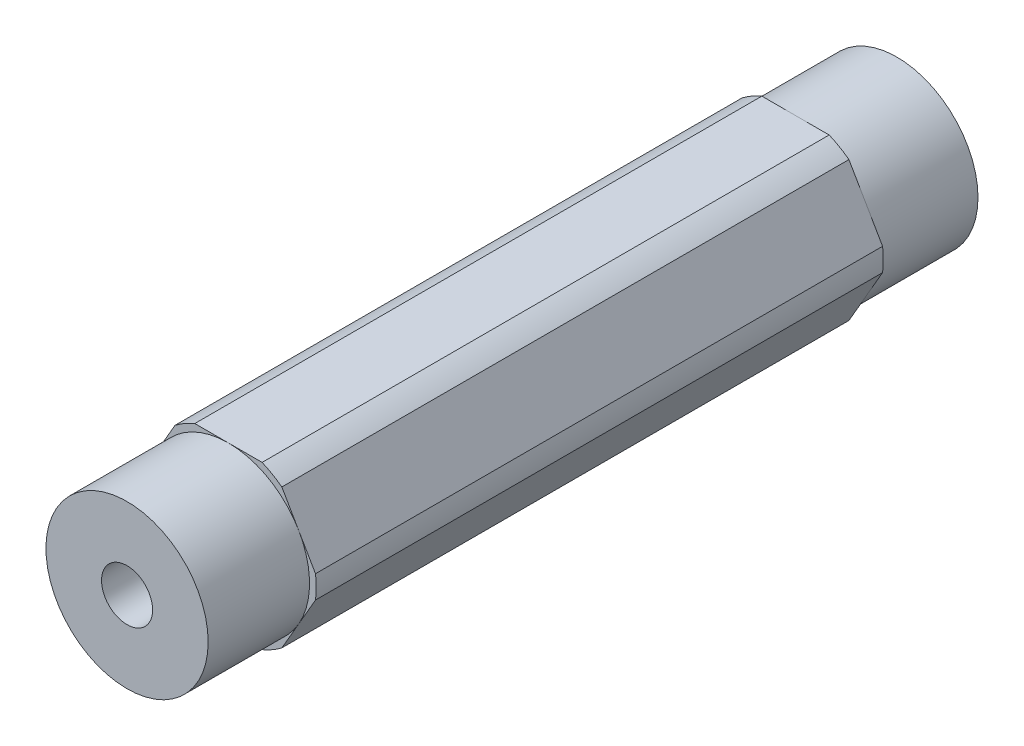
SolidWorks part; units mm, degrees
material "6061-T6 (SS)"
ref_plane "Front Plane" through (0, 0, 0) normal (0, 0, 1) x (1, 0, 0)
ref_plane "Top Plane" through (0, 0, 0) normal (0, 1, 0) x (1, 0, 0)
ref_plane "Right Plane" through (0, 0, 0) normal (1, 0, 0) x (0, 0, -1)
sketch "Sketch1" plane through (0, 0, 0) normal (0, 0, 1) x (1, 0, 0)
  line L1 (3.6662, 6.35) -> (-3.6662, 6.35)
  line L2 (-3.6662, 6.35) -> (-7.3323, 0)
  line L3 (-7.3323, 0) -> (-3.6662, -6.35)
  line L4 (-3.6662, -6.35) -> (3.6662, -6.35)
  line L5 (3.6662, -6.35) -> (7.3323, 0)
  line L6 (7.3323, 0) -> (3.6662, 6.35)
  circle A0 centre (0, 0) radius 6.35 construction
  circle A1 centre (0, 0) radius 2
  circle A2 centre (0, 0) radius 6.875
  point P1 (0, 6.35)
  dimension "D2" = 13.75
  dimension "D3" = 4
  dimension "D1" = 12.7
extrude "Boss-Extrude1" add sketch "Sketch1" along normal mid plane 44.3992 contours L6 A2 L1 L2 L3 L4 L5 A1
sketch "Sketch4" plane through (0, 0, 22.1996) normal (0, 0, 1) x (1, 0, 0)
  circle A0 centre (0, 0) radius 6.35
  circle A1 centre (0, 0) radius 2 construction
  circle A2 centre (0, 0) radius 2
  dimension "D1" = 12.7
extrude "Boss-Extrude2" add sketch "Sketch4" along normal blind 7.9375
mirror "Mirror1" about plane through (0, 0, 0) normal (0, 0, 1) of "Boss-Extrude2"
equation "\"D2@Sketch1\"=13.75mm"
equation "\"D3@Sketch1\"=4mm"
